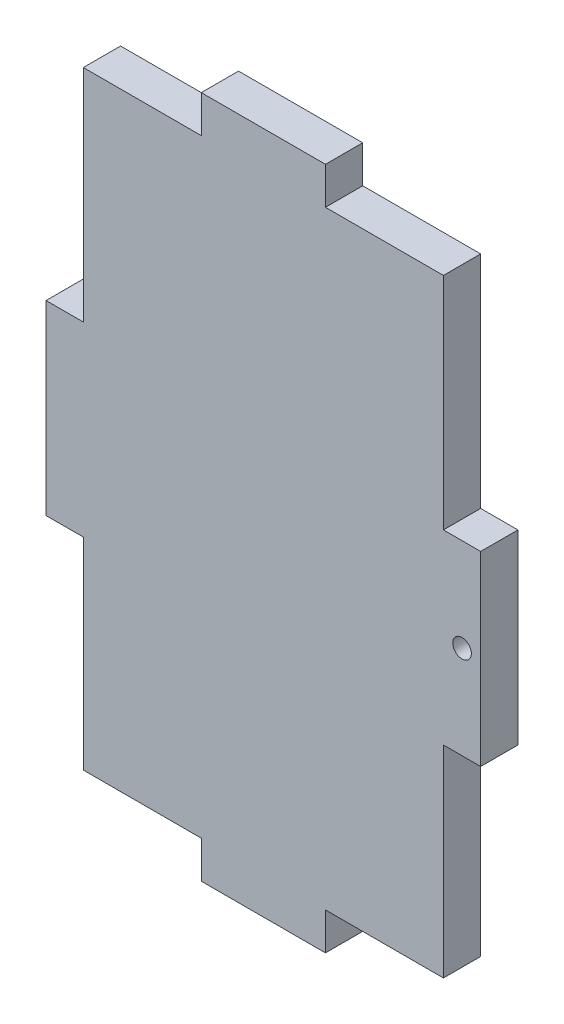
SolidWorks part; units mm, degrees
ref_plane "Plan de face" through (0, 0, 0) normal (0, 0, 1) x (1, 0, 0)
ref_plane "Plan de dessus" through (0, 0, 0) normal (0, 1, 0) x (1, 0, 0)
ref_plane "Plan de droite" through (0, 0, 0) normal (1, 0, 0) x (0, 0, -1)
sketch "Esquisse1" plane through (0, 0, 0) normal (0, 0, 1) x (1, 0, 0)
  line L1 (0, 0) -> (-70, 0)
  line L2 (0, 0) -> (0, 110)
  line L3 (0, 110) -> (-70, 110)
  line L4 (-70, 0) -> (-70, 110)
  dimension "D1" = 110
  dimension "D2" = 70
extrude "Boss.-Extru.1" add sketch "Esquisse1" along normal blind 6
sketch "Esquisse2" plane through (0, 0, 0) normal (0, 0, -1) x (-1, 0, 0)
  line L0 (0, 110) -> (70, 110) construction
  line L1 (0, 110) -> (25, 110)
  line L2 (0, 110) -> (0, 68.5)
  line L3 (6, 104) -> (25, 104)
  line L4 (25, 110) -> (25, 104)
  line L5 (70, 110) -> (45, 110)
  line L6 (0, 0) -> (25, 0)
  line L7 (64, 104) -> (45, 104)
  line L8 (45, 110) -> (45, 104)
  line L9 (70, 110) -> (70, 0) construction
  line L10 (45, 0) -> (70, 0)
  line L11 (70, 110) -> (70, 68.5)
  line L12 (70, 0) -> (70, 38.5)
  line L13 (0, 68.5) -> (6, 68.5)
  line L14 (6, 104) -> (6, 68.5)
  line L16 (0, 0) -> (0, 38.5)
  line L17 (0, 38.5) -> (6, 38.5)
  line L18 (6, 6) -> (6, 38.5)
  line L21 (6, 6) -> (25, 6)
  line L22 (25, 0) -> (25, 6)
  line L25 (64, 6) -> (45, 6)
  line L26 (45, 0) -> (45, 6)
  line L29 (70, 38.5) -> (64, 38.5)
  line L30 (64, 6) -> (64, 38.5)
  line L33 (70, 68.5) -> (64, 68.5)
  line L34 (64, 104) -> (64, 68.5)
  dimension "D1" = 6
  dimension "D2" = 20
  dimension "D3" = 6
  dimension "D4" = 25
  dimension "D5" = 6
  dimension "D6" = 30
  dimension "D7" = 41.5
  dimension "D8" = 6
  dimension "D9" = 6
  dimension "D10" = 6
  dimension "D11" = 41.5
  dimension "D12" = 19
  dimension "D13" = 20
  dimension "D14" = 6
  dimension "D15" = 30
  dimension "D16" = 6
extrude "Enlèv. mat.-Extru.1" cut sketch "Esquisse2" against normal through all
sketch "Esquisse3" plane through (0, 0, 0) normal (0, 0, -1) x (-1, 0, 0)
  line L0 (0, 38.5) -> (0, 68.5) construction
  line L1 (0, 68.5) -> (6, 68.5) construction
  circle A0 centre (3, 53.5) radius 1.5
  dimension "D1" = 3
  dimension "D2" = 3
  dimension "D3" = 15
extrude "Enlèv. mat.-Extru.2" cut sketch "Esquisse3" against normal through all
sketch "Esquisse4" plane through (0, 0, 0) normal (0, 0, -1) x (-1, 0, 0)
  circle A0 centre (3, 53.5) radius 2.995
  dimension "D1" = 5.99
extrude "Enlèv. mat.-Extru.3" cut sketch "Esquisse4" against normal blind 3
